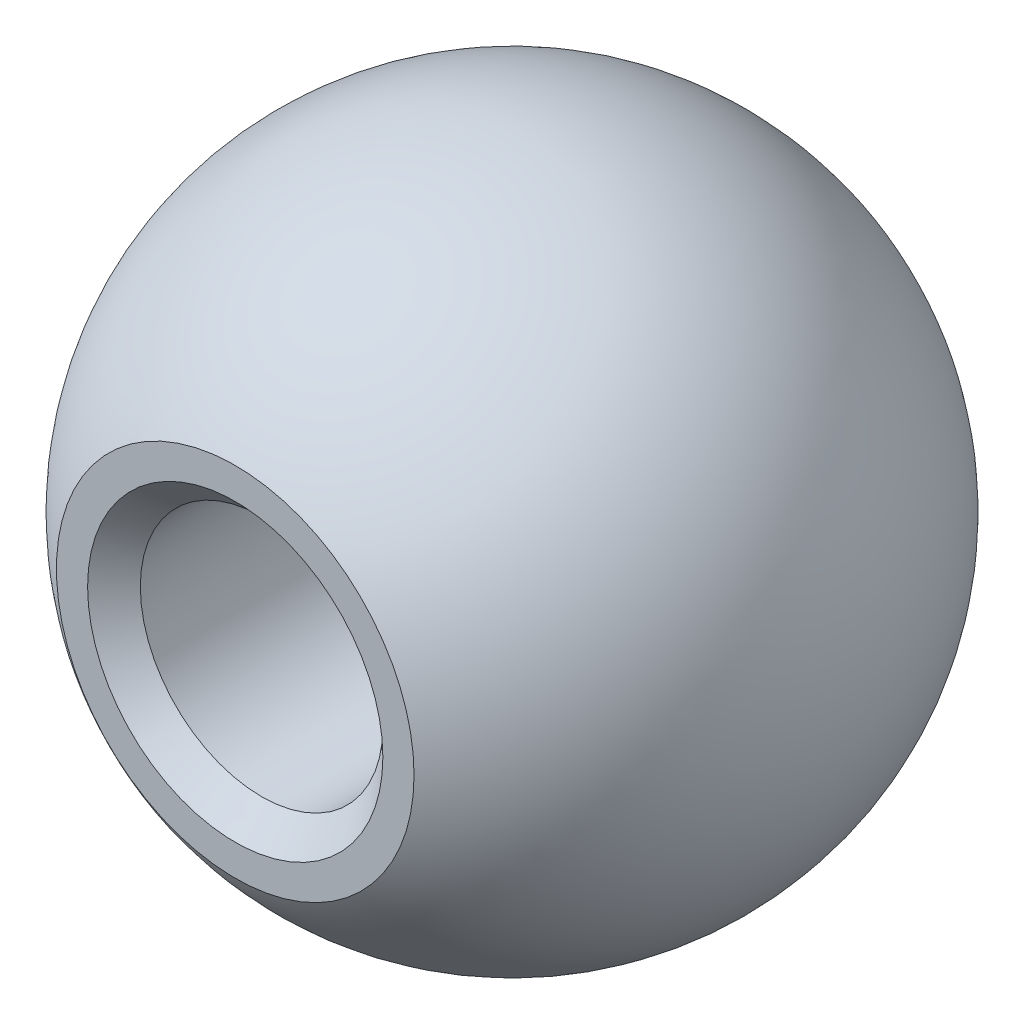
SolidWorks part; units mm, degrees
ref_plane "Front Plane" through (0, 0, 0) normal (0, 0, 1) x (1, 0, 0)
ref_plane "Top Plane" through (0, 0, 0) normal (0, 1, 0) x (1, 0, 0)
ref_plane "Right Plane" through (0, 0, 0) normal (1, 0, 0) x (0, 0, -1)
sketch "Sketch1" plane through (0, 0, 0) normal (0, 0, 1) x (1, 0, 0)
  line L0 (0, 25.5203) -> (0, -25.5203) construction
  line L1 (0, 12.5) -> (0, -12.5)
  arc A0 (0, 12.5) -> (0, -12.5) centre (0, 0) ccw
  dimension "D1" = 25
revolve "Revolve1" add sketch "Sketch1" angle 360 about L1
ref_plane "Plane1" through (0, 0, 12.5) normal (0, 0, 1) x (1, 0, 0)
sketch "Sketch2" plane through (0, 0, 12.5) normal (0, 0, 1) x (1, 0, 0)
  circle A0 centre (0, 0) radius 20
  dimension "D1" = 40
extrude "Cut-Extrude1" cut sketch "Sketch2" against normal blind 2
hole_wizard "M10x0.75 Tapped Hole1" positions "Sketch5" profile "Sketch6" tap size "M10x0.75" standard "DIN"
sketch "Sketch5" plane through (0, 0, 10.5) normal (0, 0, 1) x (1, 0, 0)
  point P0 (0, 0)
sketch "Sketch6" plane through (0, 0, 10.5) normal (1, 0, 0) x (0, -1, 0)
  line L0 (0, 0) -> (0, 14.764)
  line L1 (0, 14.764) -> (4.6, 12)
  line L2 (4.6, 12) -> (4.6, 0)
  line L5 (4.6, 0) -> (0, 0)
  line L10 (0, 14.764) -> (-4.6, 12) construction
  line L11 (0, -6.35) -> (0, 107.95) construction
  dimension "Tap Drill Dia." = 9.2
  dimension "Tap Drill Depth" = 12
  dimension "Drill Angle" = 118
cosmetic thread "Hole Thread1" parameters "D1"=10, "D2"=10
chamfer "Chamfer1" distance 1 angle 45 1 edges at (4.6, 0, 10.5)
